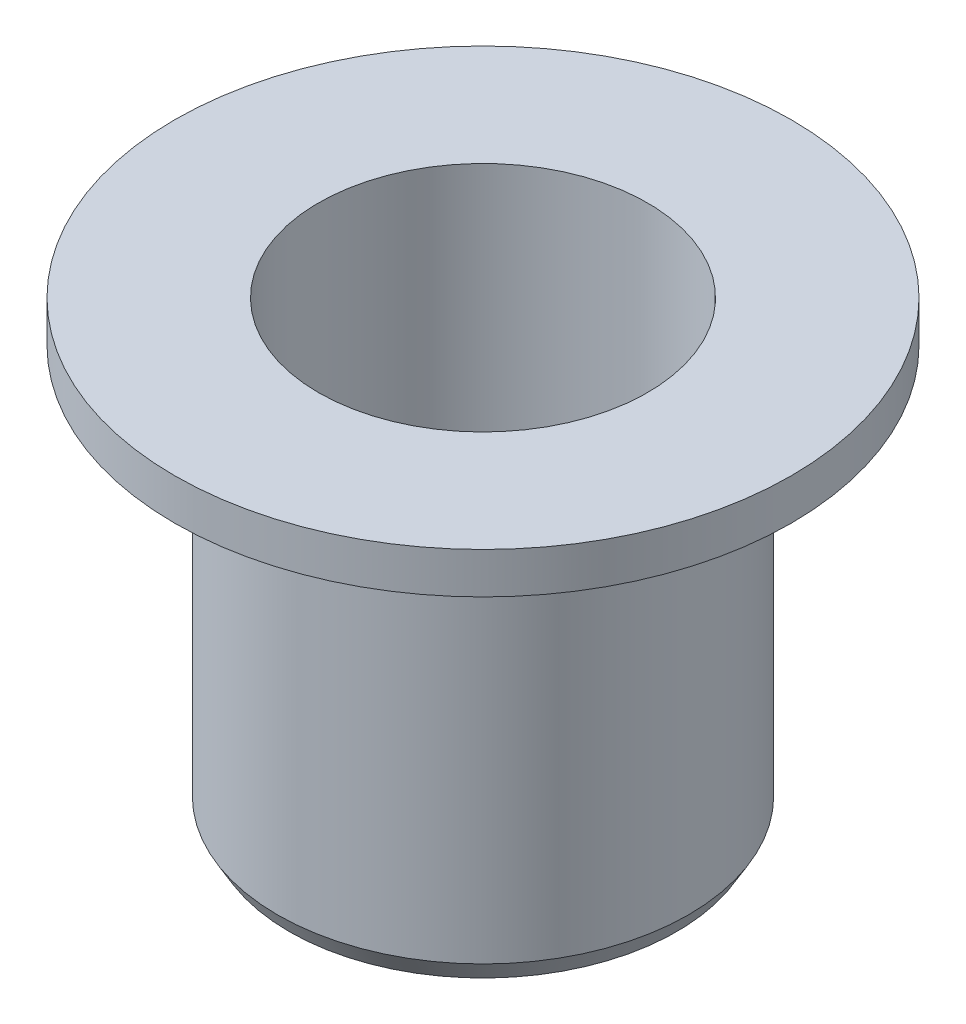
SolidWorks part; units mm, degrees
ref_plane "Front Plane" through (0, 0, 0) normal (0, 0, 1) x (1, 0, 0)
ref_plane "Top Plane" through (0, 0, 0) normal (0, 1, 0) x (1, 0, 0)
ref_plane "Right Plane" through (0, 0, 0) normal (1, 0, 0) x (0, 0, -1)
sketch "Sketch1" plane through (0, 0, 0) normal (0, 0, 1) x (1, 0, 0)
  line L0 (-7.5, 0) -> (-7.5, -1)
  line L1 (-7.5, -1) -> (-5.5, -1)
  line L2 (-5, -1.5) -> (-5, -10.5)
  line L3 (-5, -10.5) -> (-4.7113, -11)
  line L4 (-4.7113, -11) -> (-4, -11)
  line L5 (-4, -11) -> (-4, 0)
  line L6 (-4, 0) -> (-7.5, 0)
  line L7 (0, 0) -> (0, -11.7253) construction
  arc A0 (-5.5, -1) -> (-5, -1.5) centre (-5.5, -1.5) cw
  dimension "D5" = 0.5
  dimension "D1" = 1
  dimension "D2" = 1
  dimension "D3" = 0.5
  dimension "D4" = 30
  dimension "D6" = 15
  dimension "D7" = 8
  dimension "D8" = 11
revolve "Revolve1" add sketch "Sketch1" angle 360 about L7
